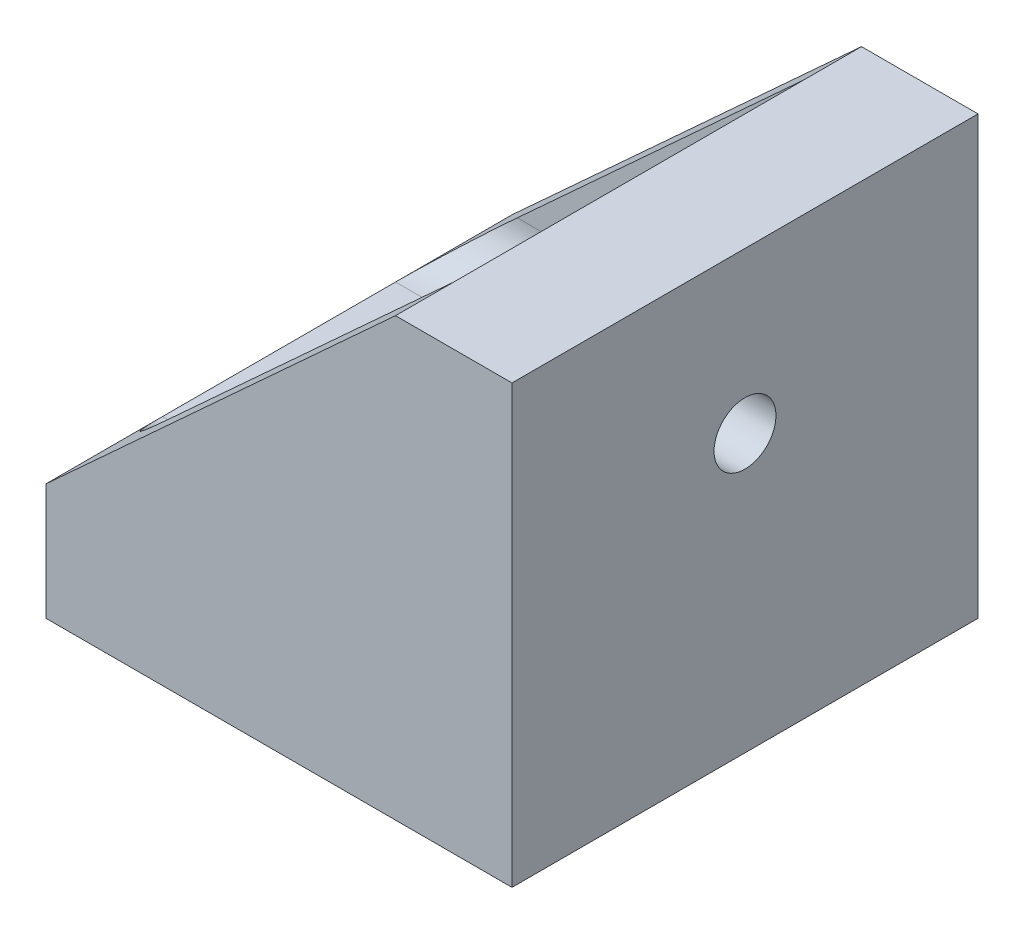
SolidWorks part; units mm, degrees
ref_plane "Front Plane" through (0, 0, 0) normal (0, 0, 1) x (1, 0, 0)
ref_plane "Top Plane" through (0, 0, 0) normal (0, 1, 0) x (1, 0, 0)
ref_plane "Right Plane" through (0, 0, 0) normal (1, 0, 0) x (0, 0, -1)
sketch "Sketch1" plane through (0, 0, 0) normal (0, 0, 1) x (1, 0, 0)
  line L1 (0, 0) -> (101.6, 0)
  line L2 (0, 0) -> (0, 25.4)
  line L3 (0, 25.4) -> (76.2, 25.4)
  line L4 (101.6, 0) -> (101.6, 25.4)
  line L6 (101.6, 25.4) -> (101.6, 95.25)
  line L7 (101.6, 95.25) -> (76.2, 95.25)
  line L8 (76.2, 25.4) -> (76.2, 95.25)
  dimension "D1" = 25.4
  dimension "D2" = 101.6
  dimension "D3" = 69.85
extrude "Boss-Extrude1" add sketch "Sketch1" along normal mid plane 101.6
sketch "Sketch2" plane through (76.2, 0, 0) normal (-1, 0, 0) x (0, 0, 1)
  line L0 (0, 25.4) -> (0, 95.25) construction
  line L1 (50.8, 25.4) -> (-50.8, 25.4) construction
  line L2 (50.8, 95.25) -> (-50.8, 95.25) construction
  point P6 (0, 60.325)
hole_wizard "CBORE for M12 Hex Head Bolt1" positions "Sketch2" profile "Sketch3" counterbore size "M12" standard "ANSI Metric" end condition through all
sketch "Sketch3" plane through (76.2, 60.325, 0) normal (0, 1, 0) x (0, 0, 1)
  line L0 (0, 0) -> (0, 25.4)
  line L1 (0, 25.4) -> (6.75, 25.4)
  line L3 (6.75, 25.4) -> (6.75, 7.95)
  line L4 (6.75, 7.95) -> (11.89, 7.95)
  line L5 (11.89, 7.95) -> (11.89, 0)
  line L7 (11.89, 0) -> (0, 0)
  line L11 (0, -6.35) -> (0, 107.95) construction
  dimension "Thru Hole Dia." = 13.5
  dimension "Thru Hole Depth" = 25.4
  dimension "C'Bore Dia." = 23.78
  dimension "C'Bore Depth" = 7.95
sketch "Sketch5" plane through (0, 0, -50.8) normal (0, 0, -1) x (-1, 0, 0)
  line L0 (-76.2, 95.25) -> (0, 25.4)
  line L1 (0, 25.4) -> (-76.2, 25.4)
  line L2 (-76.2, 25.4) -> (-76.2, 95.25)
extrude "Boss-Extrude2" add sketch "Sketch5" against normal blind 12.7
mirror "Mirror1" about plane through (0, 0, 0) normal (0, 0, 1) of "Boss-Extrude2"
fillet "Fillet1" radius 12.7 3 edges at (38.1, 25.4, -38.1) (38.1, 25.4, 38.1) (76.2, 25.4, 0)
